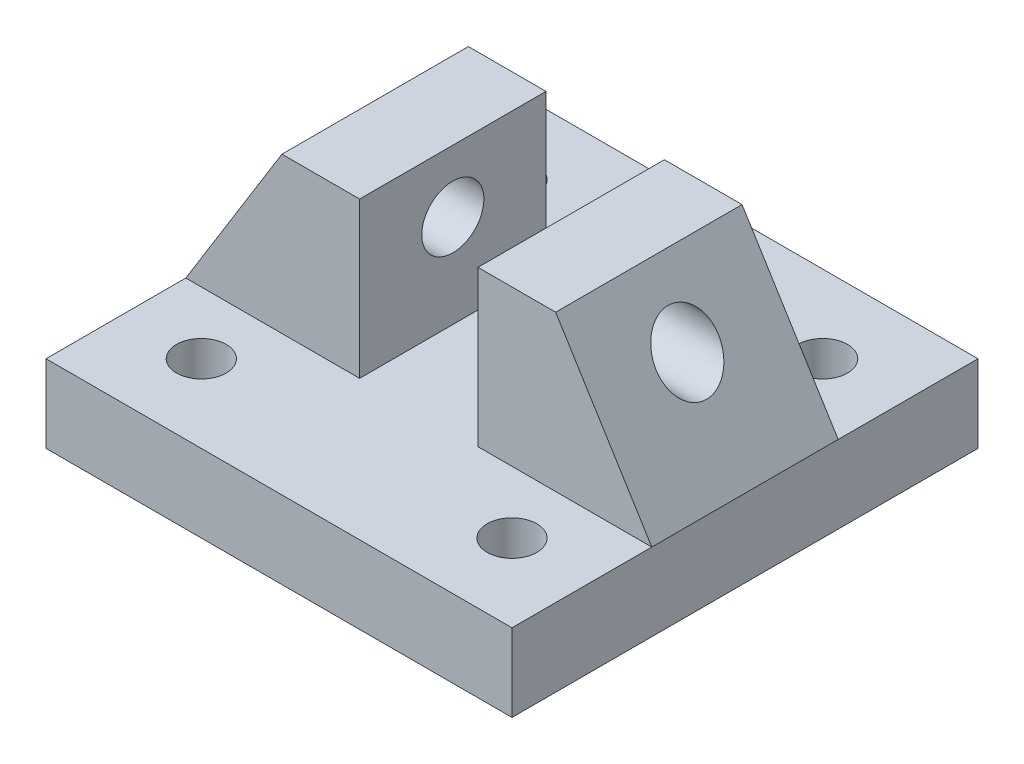
SolidWorks part; units mm, degrees
ref_plane "Front Plane" through (0, 0, 0) normal (0, 0, 1) x (1, 0, 0)
ref_plane "Top Plane" through (0, 0, 0) normal (0, 1, 0) x (1, 0, 0)
ref_plane "Right Plane" through (0, 0, 0) normal (1, 0, 0) x (0, 0, -1)
sketch "Sketch1" plane through (0, 0, 0) normal (0, 1, 0) x (1, 0, 0)
  line L1 (-15, 15) -> (15, 15)
  line L2 (-15, 15) -> (-15, -15)
  line L3 (-15, -15) -> (15, -15)
  line L4 (15, 15) -> (15, -15)
  line L5 (-15, 15) -> (15, -15) construction
  line L6 (-15, -15) -> (15, 15) construction
  point P0 (0, 0)
  dimension "D1" = 30
  dimension "D2" = 30
extrude "Boss-Extrude1" add sketch "Sketch1" along normal blind 5
sketch "Sketch2" plane through (0, 0, 0) normal (0, 0, 1) x (1, 0, 0)
  line L0 (15, 0) -> (-15, 0)
  line L1 (-15, 0) -> (-15, 5)
  line L2 (-15, 5) -> (-8.81, 15)
  line L3 (-8.81, 15) -> (-3.81, 15)
  line L4 (-3.81, 15) -> (-3.81, 5)
  line L5 (-15, 5) -> (15, 5) construction
  line L6 (-3.81, 5) -> (3.81, 5)
  line L7 (0, 0) -> (0, 21.7905) construction
  line L8 (3.81, 15) -> (3.81, 5)
  line L9 (8.81, 15) -> (3.81, 15)
  line L10 (15, 5) -> (8.81, 15)
  line L11 (15, 0) -> (15, 5)
  point P11 (0, 5)
  dimension "D1" = 7.62
  dimension "D2" = 10
  dimension "D3" = 5
extrude "Boss-Extrude2" add sketch "Sketch2" along normal blind 6 and the other way blind 6
hole_wizard "M3 Clearance Hole1" positions "Sketch3" profile "Sketch4" hole size "M3" standard "ANSI Metric" end condition through all
sketch "Sketch3" plane through (0, 5, 0) normal (0, 1, 0) x (1, 0, 0)
  line L0 (0, 0) -> (0, 29.0877) construction
  line L2 (0, 0) -> (18.5867, 0) construction
  point P0 (-10, 10)
  point P9 (10, 10)
  point P16 (10, -10)
  point P17 (-10, -10)
  dimension "D1" = 20
  dimension "D2" = 20
sketch "Sketch4" plane through (-10, 5, -10) normal (1, 0, 0) x (0, 0, 1)
  line L0 (0, 0) -> (0, 5)
  line L1 (0, 5) -> (1.6, 5)
  line L2 (1.6, 5) -> (1.6, 0)
  line L5 (1.6, 0) -> (0, 0)
  line L11 (0, -6.35) -> (0, 107.95) construction
  dimension "Thru Hole Dia." = 3.2
  dimension "Thru Hole Depth" = 5
sketch "Sketch5" plane through (0, 0, 0) normal (1, 0, 0) x (0, 0, -1)
  line L0 (0, 0) -> (0, 25.0605) construction
  circle A0 centre (0, 11) radius 2
  dimension "D1" = 4
  dimension "D2" = 11
extrude "Cut-Extrude1" cut sketch "Sketch5" against normal blind 8 and the other way through all
